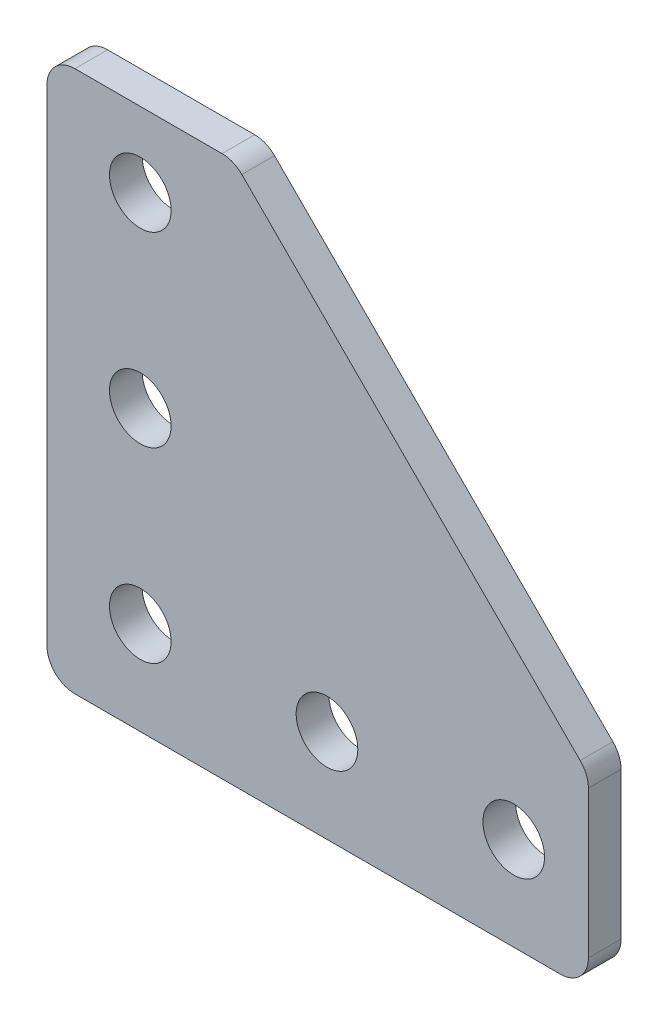
SolidWorks part; units mm, degrees
material "Liga de aço"
ref_plane "Plano frontal" through (0, 0, 0) normal (0, 0, 1) x (1, 0, 0)
ref_plane "Plano superior" through (0, 0, 0) normal (0, 1, 0) x (1, 0, 0)
ref_plane "Plano direito" through (0, 0, 0) normal (1, 0, 0) x (0, 0, -1)
sketch "Esboço1" plane through (0, 0, 0) normal (0, 0, 1) x (1, 0, 0)
  line L0 (-9, 29) -> (29, -9)
  line L1 (-29, 29) -> (29, 29)
  line L2 (-29, 29) -> (-29, -29)
  line L3 (-29, -29) -> (29, -29)
  line L4 (29, 29) -> (29, -29)
  line L5 (-29, 29) -> (29, -29) construction
  line L6 (-29, -29) -> (29, 29) construction
  point P0 (0, 0)
  dimension "D1" = 58
  dimension "D2" = 58
  dimension "D3" = 20
  dimension "D4" = 20
extrude "Ressalto-extrusão1" add sketch "Esboço1" along normal mid plane 3.5 contours L4 L0 L1 L2 L3
sketch "Esboço2" plane through (0, 0, 1.75) normal (0, 0, 1) x (1, 0, 0)
  line L2 (-29, -29) -> (29, -29) construction
  line L3 (-29, 29) -> (-29, -29) construction
  circle A0 centre (-19, -19) radius 3.3
  circle A1 centre (1, -19) radius 3.3
  circle A2 centre (21, -19) radius 3.3
  circle A3 centre (-19, 1) radius 3.3
  circle A4 centre (-19, 21) radius 3.3
  dimension "D1" = 6.6
  dimension "D2" = 10
  dimension "D3" = 10
  dimension "D4" = 3
  dimension "D5" = 3
extrude "Corte-extrusão1" cut sketch "Esboço2" against normal through all
fillet "Filete1" radius 3 5 edges at (-9, 29, 0) (29, -9, 0) (29, -29, 0) (-29, -29, 0) (-29, 29, 0)
